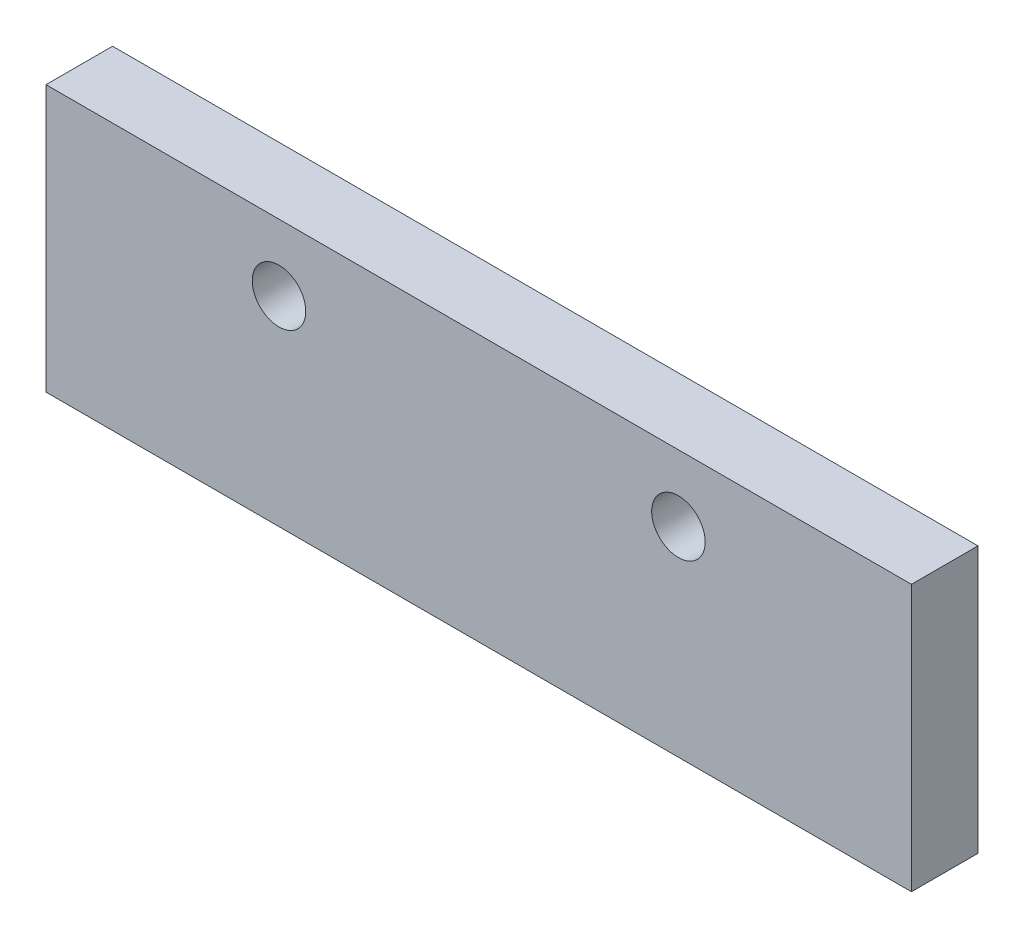
SolidWorks part; units mm, degrees
material "6061 Alloy"
ref_plane "Front Plane" through (0, 0, 0) normal (0, 0, 1) x (1, 0, 0)
ref_plane "Top Plane" through (0, 0, 0) normal (0, 1, 0) x (1, 0, 0)
ref_plane "Right Plane" through (0, 0, 0) normal (1, 0, 0) x (0, 0, -1)
sketch "Sketch1" plane through (0, 0, 0) normal (0, 0, 1) x (1, 0, 0)
  line L1 (0, 0) -> (82.55, 0)
  line L2 (0, 0) -> (0, 25.4)
  line L3 (0, 25.4) -> (82.55, 25.4)
  line L4 (82.55, 0) -> (82.55, 25.4)
  dimension "D1" = 82.55
  dimension "D2" = 25.4
extrude "Boss-Extrude1" add sketch "Sketch1" against normal blind 6.35
hole_wizard "1/4-20 Tapped Hole1" positions "Sketch2" profile "Sketch3" tap size "1/4-20" standard "ANSI Inch" end condition through all
sketch "Sketch2" plane through (0, 0, 0) normal (0, 0, 1) x (1, 0, 0)
  line L0 (82.55, 25.4) -> (0, 25.4) construction
  line L1 (0, 25.4) -> (0, 0) construction
  line L2 (82.55, 0) -> (82.55, 25.4) construction
  point P0 (22.225, 19.05)
  point P2 (60.325, 19.05)
  dimension "D1" = 6.35
  dimension "D2" = 6.35
  dimension "D3" = 22.225
  dimension "D4" = 22.225
sketch "Sketch3" plane through (22.225, 19.05, 0) normal (1, 0, 0) x (0, -1, 0)
  line L0 (0, 0) -> (0, 6.35)
  line L1 (0, 6.35) -> (2.5527, 6.35)
  line L2 (2.5527, 6.35) -> (2.5527, 0)
  line L5 (2.5527, 0) -> (0, 0)
  line L11 (0, -6.35) -> (0, 107.95) construction
  dimension "Thru Tap Drill Dia." = 5.1054
  dimension "Thru Tap Drill Depth" = 6.35
cosmetic thread "Hole Thread1"
cosmetic thread "Hole Thread2"
